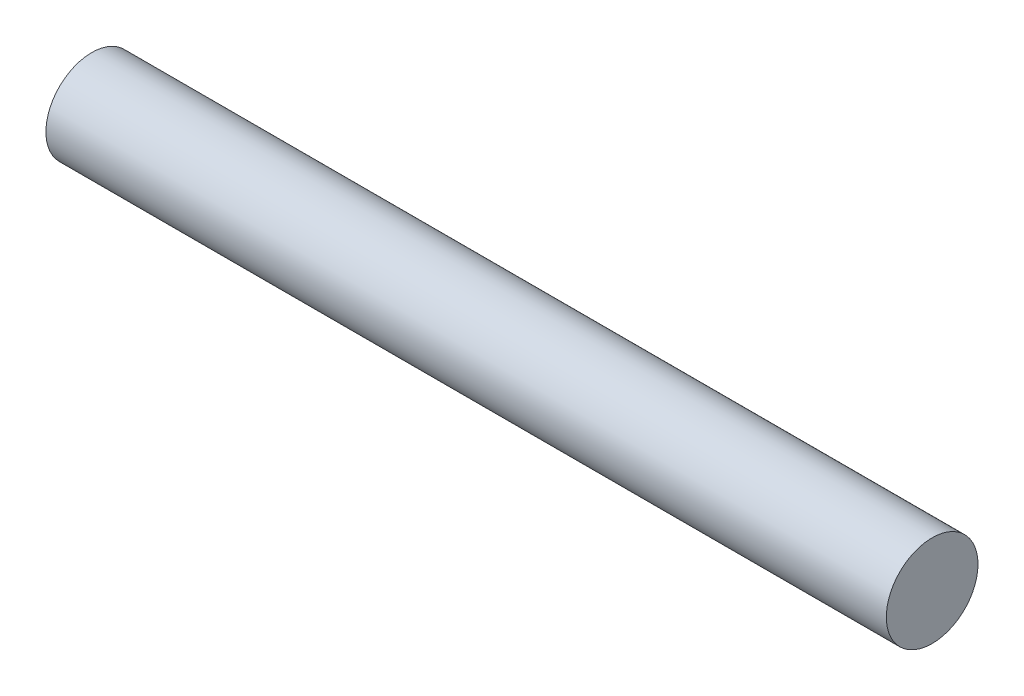
SolidWorks part; units mm, degrees
material "2024 Alaşım"
ref_plane "Ön Düzlem" through (0, 0, 0) normal (0, 0, 1) x (1, 0, 0)
ref_plane "Üst Düzlem" through (0, 0, 0) normal (0, 1, 0) x (1, 0, 0)
ref_plane "Sağ Düzlem" through (0, 0, 0) normal (1, 0, 0) x (0, 0, -1)
sketch "Çizim1" plane through (0, 0, 0) normal (1, 0, 0) x (0, 0, -1)
  circle A0 centre (0, 0) radius 6
  dimension "D1" = 12
extrude "Yükseklik-Ekstrüzyon1" add sketch "Çizim1" along normal blind 110
